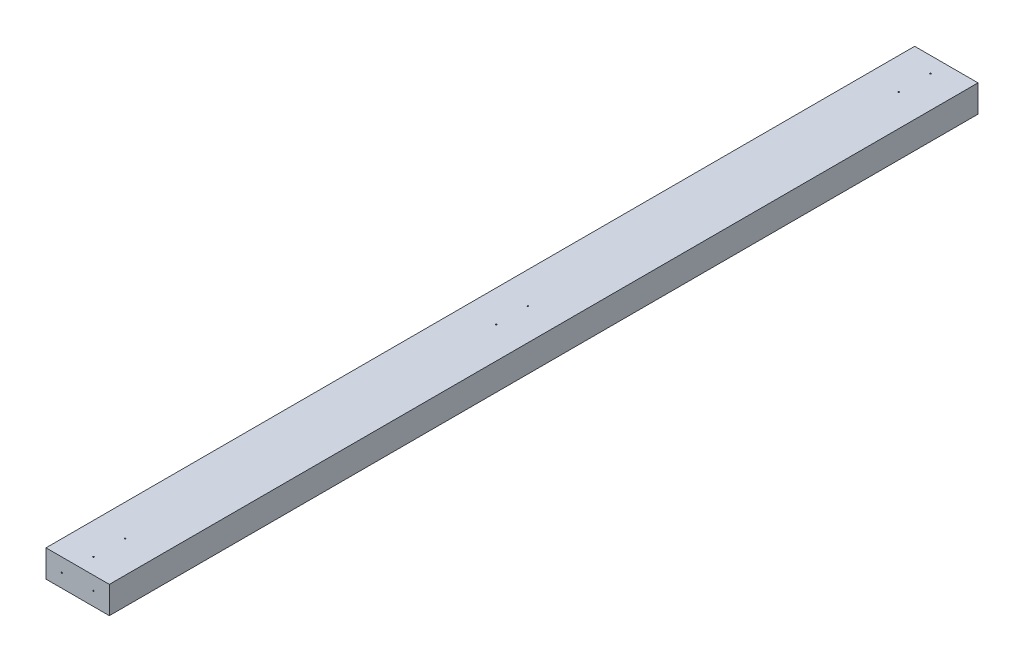
SolidWorks part; units mm, degrees
material "Pine"
ref_plane "Front Plane" through (0, 0, 0) normal (0, 0, 1) x (1, 0, 0)
ref_plane "Top Plane" through (0, 0, 0) normal (0, 1, 0) x (1, 0, 0)
ref_plane "Right Plane" through (0, 0, 0) normal (1, 0, 0) x (0, 0, -1)
sketch "Sketch1" plane through (0, 0, 0) normal (0, 0, 1) x (1, 0, 0)
  line L1 (0, 0) -> (88.9, 0)
  line L2 (0, 0) -> (0, 38.1)
  line L3 (0, 38.1) -> (88.9, 38.1)
  line L4 (88.9, 0) -> (88.9, 38.1)
  dimension "D1" = 88.9
  dimension "D2" = 38.1
extrude "Boss-Extrude1" add sketch "Sketch1" along normal blind 1219.2
sketch "Sketch2" plane through (0, 0, 0) normal (0, 0, -1) x (-1, 0, 0)
  line L1 (-88.9, 0) -> (-88.9, 38.1) construction
  line L2 (0, 38.1) -> (0, 0) construction
  line L3 (-44.45, 19.05) -> (-88.9, 19.05) construction
  line L4 (-44.45, 19.05) -> (0, 19.05) construction
  circle A0 centre (-66.675, 19.05) radius 0.8763
  circle A1 centre (-22.225, 19.05) radius 0.8763
  dimension "D1" = 1.7526
extrude "Cut-Extrude1" cut sketch "Sketch2" against normal up to surface (1219.2 mm away) up to face at (44.45, 19.05, 1219.2)
sketch "Sketch3" plane through (0, 0, 0) normal (0, -1, 0) x (1, 0, 0)
  line L0 (44.45, 1219.2) -> (44.45, 1174.75) construction
  line L1 (0, 1219.2) -> (88.9, 1219.2) construction
  line L2 (44.45, 1174.75) -> (44.45, 1130.3) construction
  line L3 (88.9, 609.6) -> (0, 609.6) construction
  line L4 (88.9, 1219.2) -> (88.9, 0) construction
  line L5 (0, 1219.2) -> (0, 0) construction
  line L6 (44.45, 609.6) -> (44.45, 654.05) construction
  line L7 (44.45, 609.6) -> (44.45, 565.15) construction
  circle A0 centre (44.45, 1196.975) radius 0.8763
  circle A1 centre (44.45, 1152.525) radius 0.8763
  circle A2 centre (44.45, 22.225) radius 0.8763
  circle A3 centre (44.45, 66.675) radius 0.8763
  circle A4 centre (44.45, 587.375) radius 0.8763
  circle A5 centre (44.45, 631.825) radius 0.8763
  dimension "D2" = 1.7526
  dimension "D4" = 1.7526
  dimension "D1" = 88.9
  dimension "D3" = 88.9
extrude "Cut-Extrude2" cut sketch "Sketch3" against normal up to surface (38.1 mm away) up to face at (44.45, 38.1, 609.6)
equation "\"length\"= 12 * 4"
equation "\"D1@Boss-Extrude1\"=\"length\""
